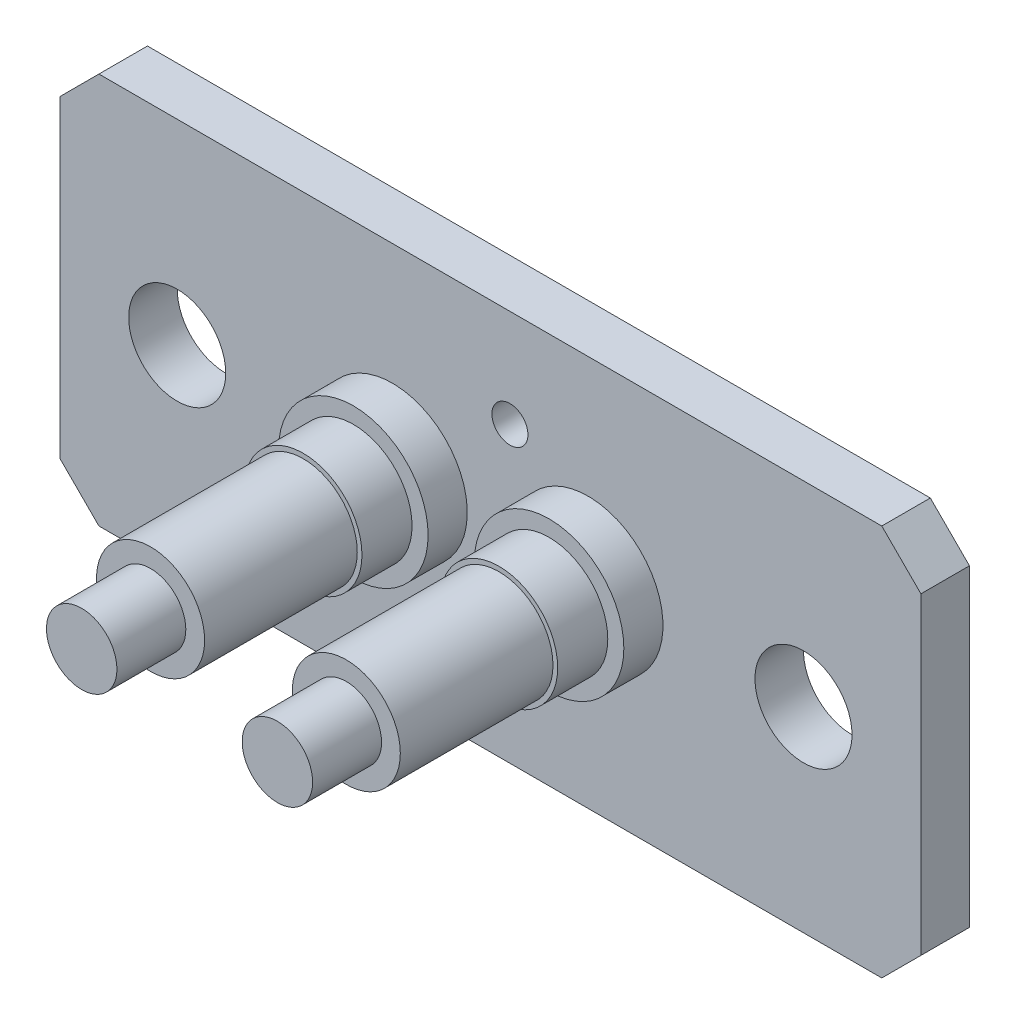
SolidWorks part; units mm, degrees
ref_plane "Front Plane" through (0, 0, 0) normal (0, 0, 1) x (1, 0, 0)
ref_plane "Top Plane" through (0, 0, 0) normal (0, 1, 0) x (1, 0, 0)
ref_plane "Right Plane" through (0, 0, 0) normal (1, 0, 0) x (0, 0, -1)
sketch "Model" plane through (0, 0, 0) normal (0, 0, 1) x (1, 0, 0)
  line L0 (0, 11.43) -> (1.27, 12.7)
  line L1 (27.94, 11.43) -> (27.94, 1.27)
  line L2 (27.94, 1.27) -> (26.67, 0)
  line L3 (0, 1.27) -> (0, 11.43)
  line L4 (1.27, 12.7) -> (26.67, 12.7)
  line L5 (26.67, 12.7) -> (27.94, 11.43)
  line L6 (1.27, 0) -> (0, 1.27)
  line L7 (26.67, 0) -> (1.27, 0)
  circle A0 centre (10.795, 6.35) radius 0.5842
  circle A1 centre (17.145, 6.35) radius 0.5842
  circle A2 centre (3.81, 6.35) radius 1.5748
  circle A3 centre (24.13, 6.35) radius 1.5748
  circle A4 centre (13.335, 3.175) radius 0.5842
  circle A5 centre (14.605, 9.525) radius 0.5842
extrude "Boss-Extrude1" add sketch "Model" along normal blind 1.5748
sketch "Sketch1" plane through (0, 0, 1.5748) normal (0, 0, 1) x (1, 0, 0)
  circle A0 centre (10.795, 6.35) radius 2.4257
  circle A1 centre (17.145, 6.35) radius 2.4257
  dimension "D1" = 4.8514
extrude "Boss-Extrude2" add sketch "Sketch1" along normal blind 1.27
sketch "Sketch2" plane through (0, 0, 1.5748) normal (0, 0, 1) x (1, 0, 0)
  circle A0 centre (10.795, 6.35) radius 1.905
  circle A1 centre (17.145, 6.35) radius 1.905
  dimension "D1" = 3.81
extrude "Boss-Extrude3" add sketch "Sketch2" along normal blind 2.8956
sketch "Sketch3" plane through (0, 0, 1.5748) normal (0, 0, 1) x (1, 0, 0)
  circle A0 centre (17.145, 6.35) radius 1.7526
  circle A1 centre (10.795, 6.35) radius 1.7526
  dimension "D1" = 3.5052
extrude "Boss-Extrude4" add sketch "Sketch3" along normal blind 7.8486
sketch "Sketch4" plane through (0, 0, 1.5748) normal (0, 0, 1) x (1, 0, 0)
  circle A0 centre (17.145, 6.35) radius 1.143
  circle A1 centre (10.795, 6.35) radius 1.143
  dimension "D1" = 2.286
extrude "Boss-Extrude5" add sketch "Sketch4" along normal blind 10.0838
sketch "Sketch5" plane through (0, 0, 1.5748) normal (0, 0, -1) x (-1, 0, 0)
  circle A0 centre (-17.145, 6.35) radius 0.508
  circle A1 centre (-10.795, 6.35) radius 0.508
  dimension "D1" = 1.016
extrude "Boss-Extrude6" add sketch "Sketch5" along normal blind 2.794
